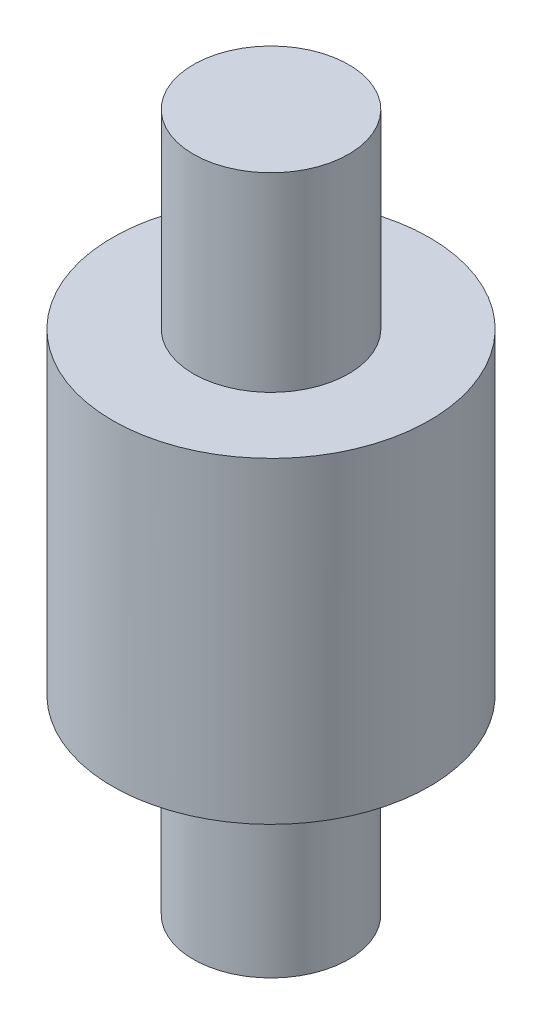
SolidWorks part; units mm, degrees
ref_plane "Front" through (0, 0, 0) normal (0, 0, 1) x (1, 0, 0)
ref_plane "Top" through (0, 0, 0) normal (0, 1, 0) x (1, 0, 0)
ref_plane "Right" through (0, 0, 0) normal (1, 0, 0) x (0, 0, -1)
sketch "Sketch2" plane through (0, 0, 0) normal (0, 1, 0) x (1, 0, 0)
  circle A0 centre (0, 0) radius 5
  dimension "D1" = 10
extrude "Boss-Extrude1" add sketch "Sketch2" along normal blind 22
sketch "Sketch3" plane through (0, 22, 0) normal (0, 1, 0) x (1, 0, 0)
  circle A0 centre (0, 0) radius 2.45
  circle A1 centre (0, 0) radius 5
  circle A2 centre (0, 0) radius 5
  circle M2 centre (0, 0) radius 5
  dimension "D2" = 4.9
  dimension "D1" = 0
extrude "Cut-Extrude1" cut sketch "Sketch3" against normal blind 6 contours A0 M2
sketch "Sketch4" plane through (0, 0, 0) normal (0, -1, 0) x (1, 0, 0)
  circle A0 centre (0, 0) radius 2.45
  circle A1 centre (0, 0) radius 5
  circle A2 centre (0, 0) radius 5
  dimension "D2" = 4.9
  dimension "D1" = 0
extrude "Cut-Extrude2" cut sketch "Sketch4" against normal blind 6
